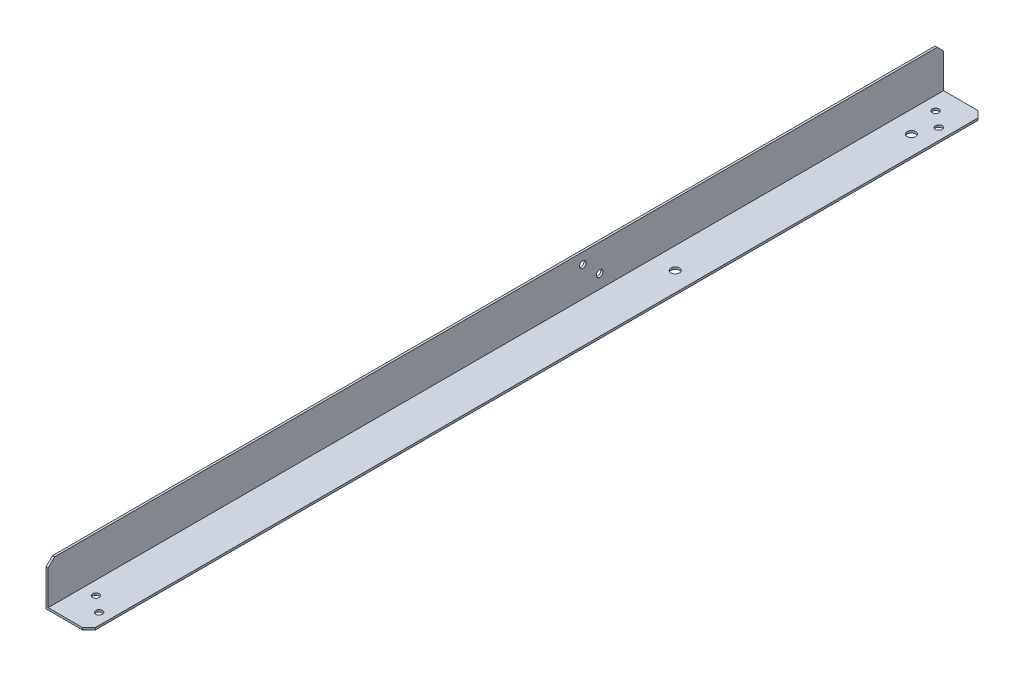
SolidWorks part; units mm, degrees
material "6061 Alloy"
ref_plane "Спереди" through (0, 0, 0) normal (0, 0, 1) x (1, 0, 0)
ref_plane "Сверху" through (0, 0, 0) normal (0, 1, 0) x (1, 0, 0)
ref_plane "Справа" through (0, 0, 0) normal (1, 0, 0) x (0, 0, -1)
sketch "Sketch1" plane through (0, 0, 0) normal (0, 0, 1) x (1, 0, 0)
  line L0 (0, 0) -> (20, 0)
  line L1 (20, 0) -> (20, 1)
  line L2 (20, 1) -> (1, 1)
  line L3 (1, 1) -> (1, 20)
  line L4 (1, 20) -> (0, 20)
  line L5 (0, 20) -> (0, 0)
  dimension "D1" = 20
  dimension "D2" = 20
  dimension "D4" = 1
extrude "Base" add sketch "Sketch1" along normal blind 417
chamfer "Chamfer1" distance 3 angle 45 4 edges at (20, 0.5, 417) (0.5, 20, 417) (0.5, 20, 0) (20, 0.5, 0)
sketch "Sketch3" plane through (1, 0, 0) normal (1, 0, 0) x (0, 0, -1)
  line L1 (-414, 1) -> (-3, 1) construction
  line L3 (0, 1) -> (0, 17) construction
  circle A0 centre (-168, 14.85) radius 1.55
  circle A1 centre (-160.2, 7.35) radius 1.55
  dimension "D1" = 3.1
  dimension "D2" = 7.5
  dimension "D3" = 6.35
  dimension "D4" = 7.8
  dimension "D5" = 168
extrude "ForCableChain" cut sketch "Sketch3" against normal blind 10
sketch "Sketch4" plane through (0, 0, 0) normal (0, -1, 0) x (1, 0, 0)
  line L0 (0, 417) -> (0, 0) construction
  line L1 (0, 0) -> (17, 0) construction
  line L2 (0, 417) -> (17, 417) construction
  circle A0 centre (7.25, 10) radius 1.55
  circle A1 centre (14.75, 16) radius 1.55
  circle A2 centre (7.25, 401) radius 1.55
  circle A3 centre (14.75, 407) radius 1.55
  dimension "D1" = 3.1
  dimension "D2" = 7.5
  dimension "D3" = 6
  dimension "D4" = 7.25
  dimension "D5" = 10
  dimension "D6" = 6
  dimension "D7" = 10
extrude "GuideHoles" cut sketch "Sketch4" against normal through all
sketch "Sketch5" plane through (0, 0, 0) normal (0, -1, 0) x (1, 0, 0)
  line L0 (0, 417) -> (0, 0) construction
  line L1 (0, 0) -> (17, 0) construction
  circle A0 centre (11, 25) radius 2
  circle A1 centre (11, 135) radius 2
  dimension "D4" = 4
  dimension "D1" = 11
  dimension "D2" = 25
  dimension "D3" = 135
extrude "CableTieHoles" cut sketch "Sketch5" against normal through all
equation "\"D1@Sketch1\"=\"D2@Sketch1\""
